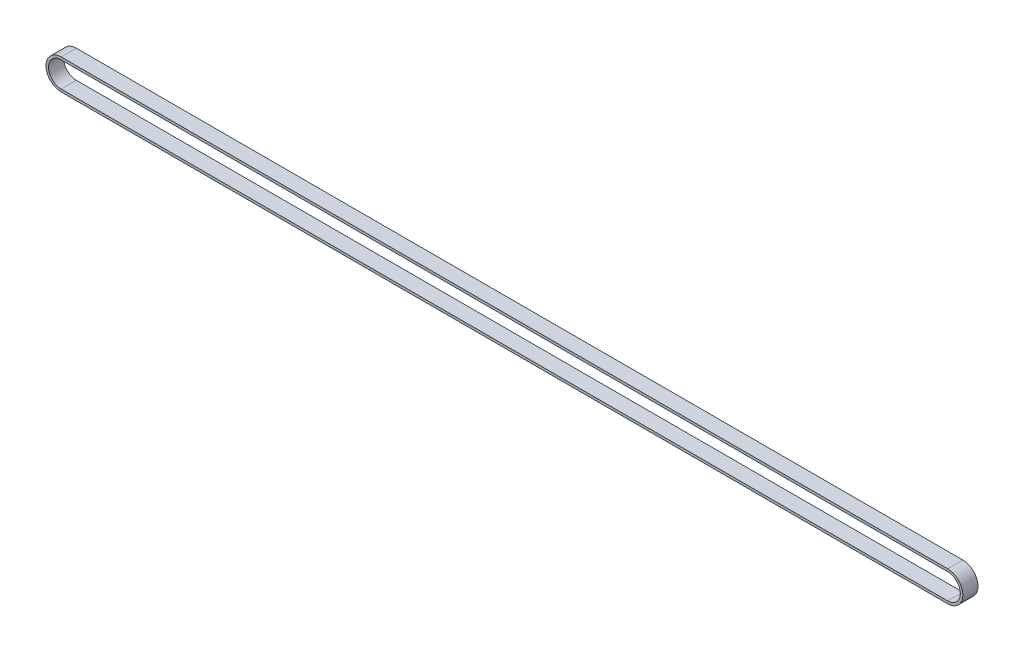
SolidWorks part; units mm, degrees
ref_plane "Front Plane" through (0, 0, 0) normal (0, 0, 1) x (1, 0, 0)
ref_plane "Top Plane" through (0, 0, 0) normal (0, 1, 0) x (1, 0, 0)
ref_plane "Right Plane" through (0, 0, 0) normal (1, 0, 0) x (0, 0, -1)
sketch "Sketch1" plane through (0, 0, 0) normal (0, 0, 1) x (1, 0, 0)
  line L0 (0, 0) -> (350.7, 0) construction
  line L1 (0, 5) -> (350.7, 5)
  line L2 (0, -5) -> (350.7, -5)
  line L3 (0, 6) -> (350.7, 6)
  line L4 (0, -6) -> (350.7, -6)
  arc A0 (0, 5) -> (0, -5) centre (0, 0) ccw
  arc A1 (350.7, -5) -> (350.7, 5) centre (350.7, 0) ccw
  arc A2 (350.7, -6) -> (350.7, 6) centre (350.7, 0) ccw
  arc A3 (0, 6) -> (0, -6) centre (0, 0) ccw
  point P3 (175.35, 0)
  dimension "D1" = 5
  dimension "D2" = 350.7
  dimension "D3" = 1
extrude "Boss-Extrude1" add sketch "Sketch1" along normal blind 6
